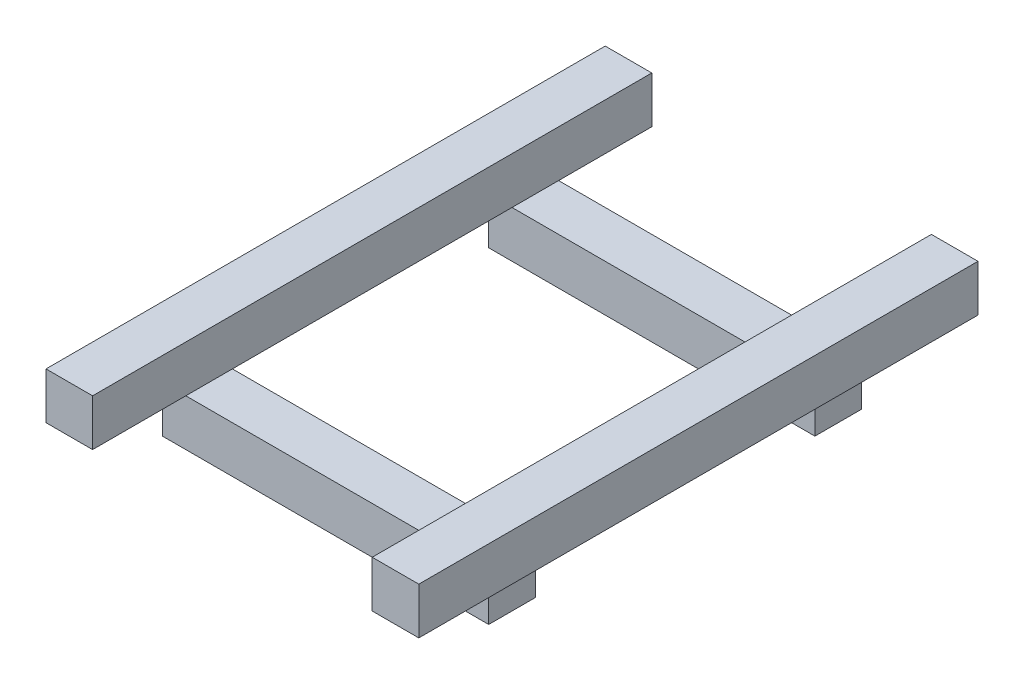
SolidWorks part; units mm, degrees
ref_plane "Front Plane" through (0, 0, 0) normal (0, 0, 1) x (1, 0, 0)
ref_plane "Top Plane" through (0, 0, 0) normal (0, 1, 0) x (1, 0, 0)
ref_plane "Right Plane" through (0, 0, 0) normal (1, 0, 0) x (0, 0, -1)
sketch "Sketch1" plane through (0, 0, 0) normal (0, 1, 0) x (1, 0, 0)
  line L1 (-131.9328, 170.7983) -> (-81.9328, 170.7983)
  line L2 (-131.9328, 170.7983) -> (-131.9328, -429.2017)
  line L3 (-131.9328, -429.2017) -> (-81.9328, -429.2017)
  line L4 (-81.9328, 170.7983) -> (-81.9328, -429.2017)
  line L9 (218.0672, 170.7983) -> (268.0672, 170.7983)
  line L10 (218.0672, 170.7983) -> (218.0672, -429.2017)
  line L11 (218.0672, -429.2017) -> (268.0672, -429.2017)
  line L12 (268.0672, 170.7983) -> (268.0672, -429.2017)
  dimension "D1" = 600
  dimension "D2" = 50
  dimension "D3" = 300
  dimension "50" = 50
extrude "Boss-Extrude1" add sketch "Sketch1" along normal blind 50
sketch "Sketch2" plane through (0, 0, 0) normal (0, -1, 0) x (-1, 0, 0)
  line L0 (131.9328, 170.7983) -> (131.9328, -429.2017) construction
  line L1 (131.9328, -329.2017) -> (-268.0672, -329.2017)
  line L2 (131.9328, -329.2017) -> (131.9328, -279.2017)
  line L3 (131.9328, -279.2017) -> (-268.0672, -279.2017)
  line L4 (-268.0672, -329.2017) -> (-268.0672, -279.2017)
  line L5 (-268.0672, -429.2017) -> (-268.0672, 170.7983) construction
  line L6 (131.9328, -429.2017) -> (81.9328, -429.2017) construction
  line L8 (131.9328, 70.7983) -> (-268.0672, 70.7983)
  line L9 (131.9328, 70.7983) -> (131.9328, 20.7983)
  line L10 (131.9328, 20.7983) -> (-268.0672, 20.7983)
  line L11 (-268.0672, 70.7983) -> (-268.0672, 20.7983)
  dimension "D1" = 350
  dimension "D2" = 100
  dimension "D3" = 50
  dimension "D4" = 50
extrude "Boss-Extrude2" add sketch "Sketch2" along normal blind 50
sketch "Sketch4" plane through (0, -50, 0) normal (0, -1, 0) x (-1, 0, 0)
  line L1 (-268.0672, -329.2017) -> (-218.0672, -329.2017) construction
  line L6 (81.9328, -329.2017) -> (131.9328, -329.2017) construction
  line L7 (-243.0672, -329.2017) -> (-268.0672, -329.2017)
  line L8 (-243.0672, -329.2017) -> (-243.0672, 70.7983)
  line L9 (-243.0672, 70.7983) -> (-268.0672, 70.7983)
  line L10 (-268.0672, -329.2017) -> (-268.0672, 70.7983)
  line L11 (106.9328, -329.2017) -> (131.9328, -329.2017)
  line L12 (106.9328, -329.2017) -> (106.9328, 70.7983)
  line L13 (106.9328, 70.7983) -> (131.9328, 70.7983)
  line L14 (131.9328, -329.2017) -> (131.9328, 70.7983)
extrude "Cut-Extrude2" cut sketch "Sketch4" against normal blind 50
